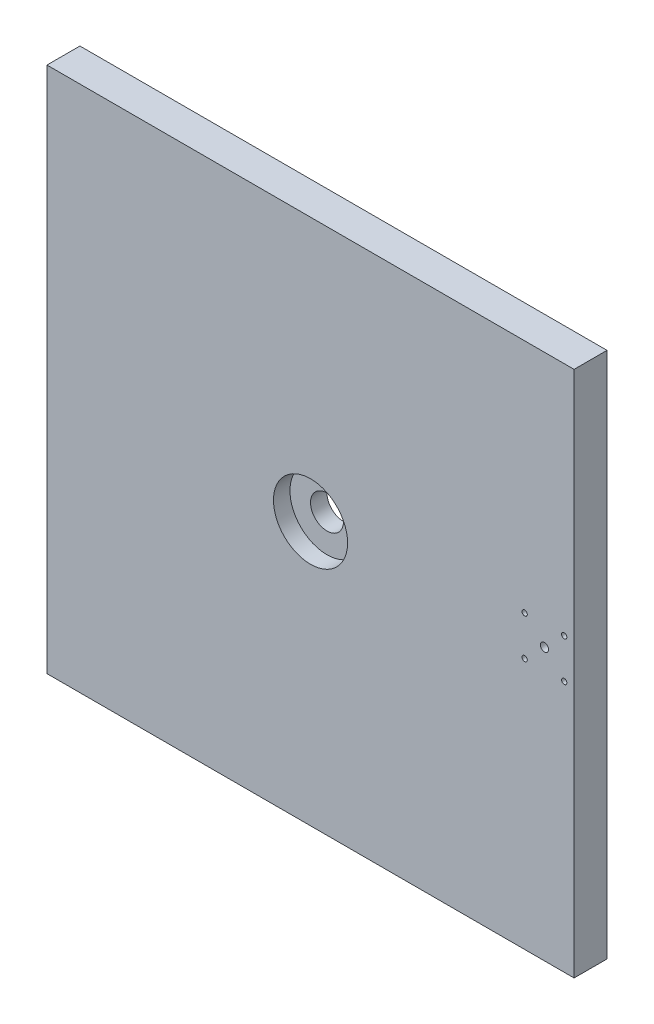
SolidWorks part; units mm, degrees
ref_plane "Front Plane" through (0, 0, 0) normal (0, 0, 1) x (1, 0, 0)
ref_plane "Top Plane" through (0, 0, 0) normal (0, 1, 0) x (1, 0, 0)
ref_plane "Right Plane" through (0, 0, 0) normal (1, 0, 0) x (0, 0, -1)
sketch "Sketch1" plane through (0, 0, 0) normal (0, 0, 1) x (1, 0, 0)
  line L1 (0, 0) -> (203.2, 0)
  line L2 (0, 0) -> (0, 203.2)
  line L3 (0, 203.2) -> (203.2, 203.2)
  line L4 (203.2, 0) -> (203.2, 203.2)
  dimension "D1" = 203.2
  dimension "D2" = 203.2
extrude "Boss-Extrude1" add sketch "Sketch1" along normal blind 12.7
hole_wizard "1/2 (0.5) Diameter Hole1" positions "Sketch2" profile "Sketch3" hole size "1/2" standard "ANSI Inch" end condition through all
sketch "Sketch2" plane through (0, 0, 12.7) normal (0, 0, 1) x (1, 0, 0)
  line L0 (203.2, 0) -> (203.2, 203.2) construction
  line L1 (0, 0) -> (203.2, 0) construction
  point P0 (101.6, 101.6)
  dimension "D1" = 101.6
  dimension "D2" = 101.6
sketch "Sketch3" plane through (101.6, 101.6, 12.7) normal (1, 0, 0) x (0, -1, 0)
  line L0 (0, 0) -> (0, 12.7)
  line L1 (0, 12.7) -> (6.35, 12.7)
  line L2 (6.35, 12.7) -> (6.35, 0)
  line L5 (6.35, 0) -> (0, 0)
  line L11 (0, -6.35) -> (0, 107.95) construction
  dimension "Thru Hole Dia." = 12.7
  dimension "Thru Hole Depth" = 12.7
sketch "Sketch7" plane through (0, 0, 12.7) normal (0, 0, 1) x (1, 0, 0)
  circle A0 centre (101.6, 101.6) radius 14.2875
  dimension "D1" = 28.575
extrude "Cut-Extrude1" cut sketch "Sketch7" against normal blind 6.35
sketch "Sketch8" plane through (0, 0, 12.7) normal (0, 0, 1) x (1, 0, 0)
  circle A0 centre (191.77, 104.7295) radius 1.5875
  circle A1 centre (101.6, 101.6) radius 6.35 construction
  circle A2 centre (184.15, 112.3495) radius 1.016
  circle A3 centre (199.39, 112.3495) radius 1.016
  circle A4 centre (199.39, 97.1095) radius 1.016
  circle A5 centre (184.15, 97.1095) radius 1.016
  point P12 (0, 0)
  point P13 (0, 0)
  point P14 (0, 0)
  point P15 (0, 0)
  point P16 (0, 0)
  dimension "D1" = 3.175
  dimension "D3" = 2.032
  dimension "D4" = 15.24
  dimension "D2" = 90.17
  dimension "D5" = 7.62
  dimension "D6" = 7.62
  dimension "D8" = 15.24
  dimension "D9" = 15.24
extrude "Cut-Extrude2" cut sketch "Sketch8" against normal through all
